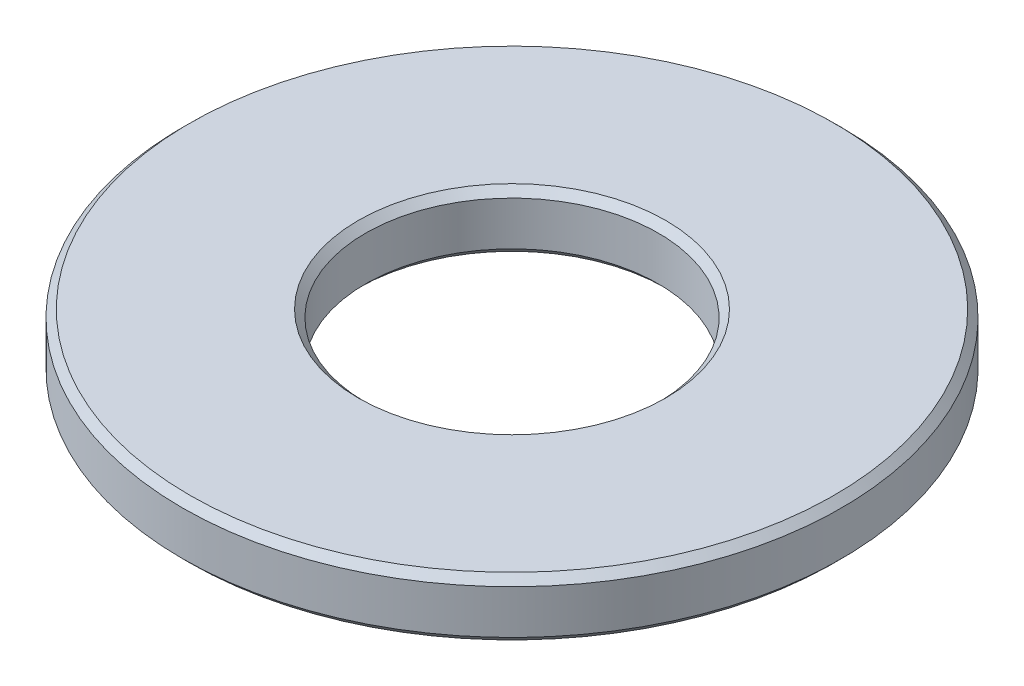
SolidWorks part; units mm, degrees
ref_plane "Alzado" through (0, 0, 0) normal (0, 0, 1) x (1, 0, 0)
ref_plane "Planta" through (0, 0, 0) normal (0, 1, 0) x (1, 0, 0)
ref_plane "Vista lateral" through (0, 0, 0) normal (1, 0, 0) x (0, 0, -1)
sketch "Croquis1" plane through (0, 0, 0) normal (0, 1, 0) x (1, 0, 0)
  circle A0 centre (0, 0) radius 2
  circle A1 centre (0, 0) radius 4.5
  dimension "D1" = 9
  dimension "D2" = 4
extrude "Saliente-Extruir1" add sketch "Croquis1" along normal blind 0.8
chamfer "Chaflán1" distance 0.1 angle 45 4 edges at (0, 0.8, 2) (0, 0.8, 4.5) (0, 0, 2) (0, 0, 4.5)
